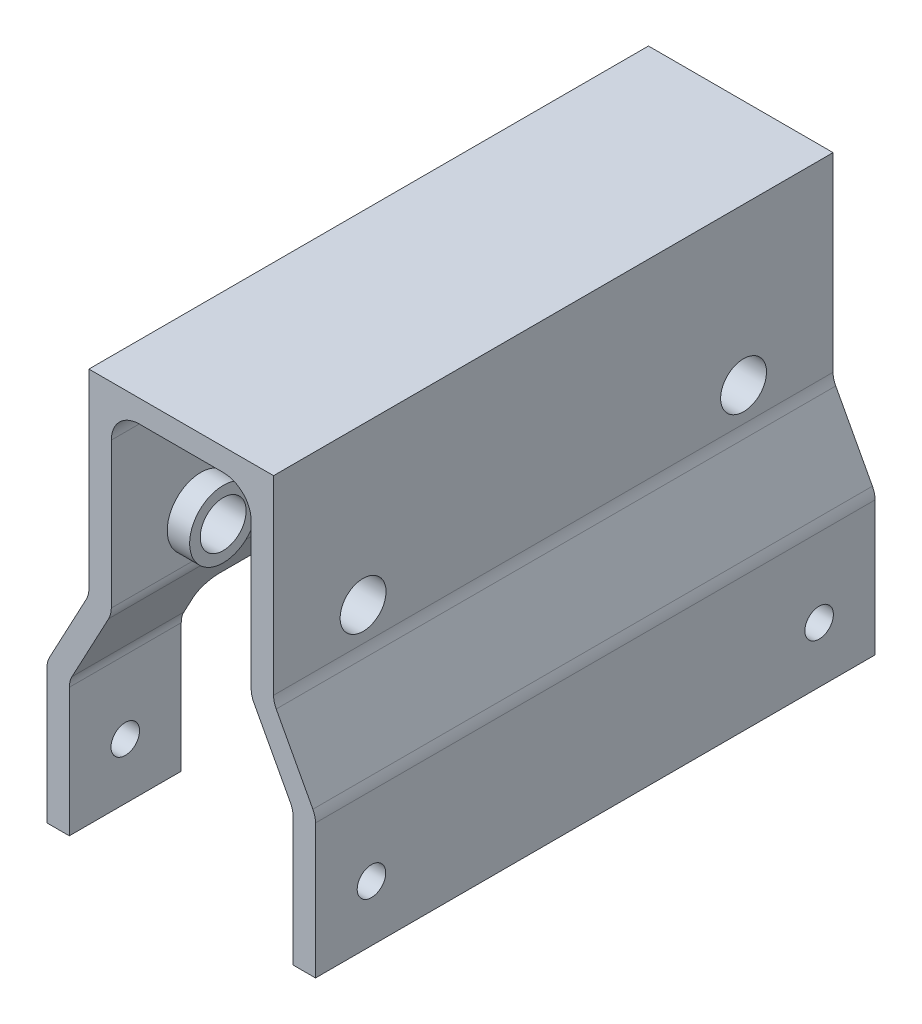
SolidWorks part; units mm, degrees
ref_plane "Front Plane" through (0, 0, 0) normal (0, 0, 1) x (1, 0, 0)
ref_plane "Top Plane" through (0, 0, 0) normal (0, 1, 0) x (1, 0, 0)
ref_plane "Right Plane" through (0, 0, 0) normal (1, 0, 0) x (0, 0, -1)
sketch "Sketch2" plane through (0, 0, 0) normal (0, 0, 1) x (1, 0, 0)
  line L0 (0, 0) -> (0, 23.9963)
  line L1 (0, 23.9963) -> (7.5, 38)
  line L2 (7.5, 38) -> (7.5, 70)
  line L3 (7.5, 70) -> (32.5, 70)
  line L4 (32.5, 70) -> (32.5, 38)
  line L5 (32.5, 38) -> (40, 23.9963)
  line L6 (40, 23.9963) -> (40, 0)
  line L7 (-4, 0) -> (-4, 25)
  line L8 (-4, 25) -> (3.5, 39.0037)
  line L9 (3.5, 39.0037) -> (3.5, 74)
  line L10 (3.5, 74) -> (36.5, 74)
  line L11 (36.5, 74) -> (36.5, 39.0037)
  line L12 (36.5, 39.0037) -> (44, 25)
  line L13 (44, 25) -> (44, 0)
  line L14 (-4, 0) -> (0, 0)
  line L15 (40, 0) -> (44, 0)
  dimension "D1" = 70
  dimension "D2" = 25
  dimension "D3" = 40
  dimension "D4" = 7.5
  dimension "D6" = 32
  dimension "D7" = 32
  dimension "D8" = 25
  dimension "D9" = 25
  dimension "D10" = 0
  dimension "D5" = 4
extrude "Boss-Extrude1" add sketch "Sketch2" along normal blind 100
sketch "Sketch3" plane through (32.5, 0, 0) normal (-1, 0, 0) x (0, 0, 1)
  line L0 (0, 70) -> (0, 38) construction
  line L1 (100, 70) -> (0, 70) construction
  line L2 (100, 70) -> (100, 38) construction
  circle A0 centre (84, 46) radius 6
  circle A1 centre (16, 46) radius 6
  dimension "D1" = 12
  dimension "D2" = 12
  dimension "D3" = 16
  dimension "D4" = 24
  dimension "D5" = 24
  dimension "D6" = 16
sketch "Sketch4" plane through (7.5, 0, 0) normal (1, 0, 0) x (0, 0, -1)
  circle A0 centre (-16, 46) radius 6 construction
  circle A1 centre (-84, 46) radius 6 construction
  circle A2 centre (-16, 46) radius 6
  circle A3 centre (-84, 46) radius 6
extrude "Boss-Extrude2" add sketch "Sketch3" along normal blind 4 contours A1 | A0
extrude "Boss-Extrude3" add sketch "Sketch4" along normal blind 4 contours A3 | A2
sketch "Sketch9" plane through (7.5, 0, 0) normal (1, 0, 0) x (0, 0, -1)
  circle A0 centre (-16, 46) radius 4.1
  circle A1 centre (-84, 46) radius 4.1
  dimension "D1" = 8.2
  dimension "D2" = 8.2
extrude "Cut-Extrude1" cut sketch "Sketch9" against normal through all both and the other way through all
sketch "Sketch10" plane through (44, 0, 0) normal (1, 0, 0) x (0, 0, -1)
  line L0 (-100, 0) -> (-100, 25) construction
  line L1 (-100, 0) -> (0, 0) construction
  line L2 (0, 0) -> (0, 25) construction
  circle A0 centre (-10, 10) radius 2.55
  circle A1 centre (-90, 10) radius 2.55
  dimension "D1" = 5.1
  dimension "D2" = 5.1
  dimension "D3" = 10
  dimension "D4" = 10
  dimension "D5" = 10
  dimension "D6" = 10
extrude "Cut-Extrude2" cut sketch "Sketch10" against normal through all both and the other way through all
sketch "Sketch13" plane through (-4, 0, 0) normal (-1, 0, 0) x (0, 0, 1)
  line L0 (100, 0) -> (0, 0) construction
  line L1 (20, 0) -> (20, 31.0037)
  line L2 (20, 31.0037) -> (80, 31.0037)
  line L3 (80, 31.0037) -> (80, 0)
  line L4 (80, 0) -> (20, 0)
  line L5 (100, 39.0037) -> (0, 39.0037) construction
  circle A0 centre (10, 10) radius 2.55 construction
  circle A1 centre (90, 10) radius 2.55 construction
  dimension "D1" = 10
  dimension "D2" = 10
  dimension "D3" = 8
extrude "Cut-Extrude5" cut sketch "Sketch13" against normal blind 24
fillet "Fillet1" radius 3 2 edges at (1.4842, 31.0037, 20) (1.4842, 31.0037, 80)
fillet "Fillet2" radius 5 2 edges at (7.5, 70, 50) (32.5, 70, 50)
fillet "Fillet3" radius 4 10 edges at (32.5, 38, 50) (40, 23.9963, 50) (44, 25, 50) (36.5, 39.0037, 50) (7.5, 38, 50) (-4, 25, 90) (-4, 25, 10) (3.5, 39.0037, 50) (0, 23.9963, 90) (0, 23.9963, 10)
